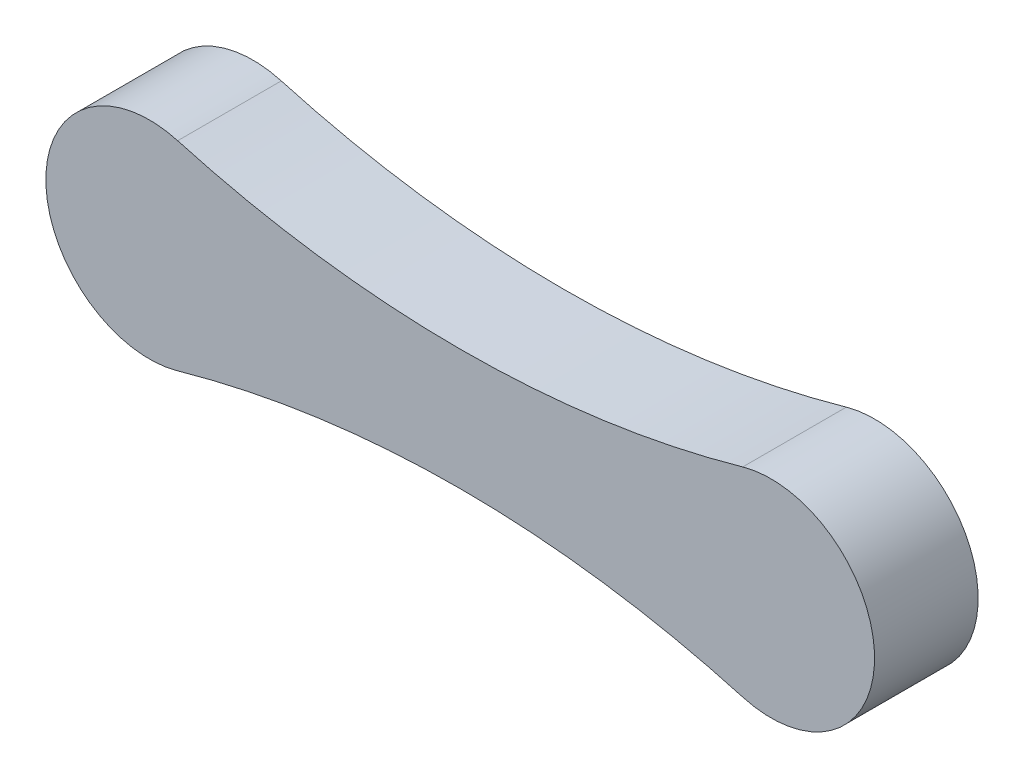
SolidWorks part; units mm, degrees
ref_plane "前视基准面" through (0, 0, 0) normal (0, 0, 1) x (1, 0, 0)
ref_plane "上视基准面" through (0, 0, 0) normal (0, 1, 0) x (1, 0, 0)
ref_plane "右视基准面" through (0, 0, 0) normal (1, 0, 0) x (0, 0, -1)
other "Configuration Table"
sketch "Sketch1" plane through (0, 0, 0) normal (0, 0, 1) x (1, 0, 0)
  line L0 (0, 0) -> (30, 0) construction
  circle A0 centre (0, 0) radius 5
  circle A2 centre (30, 0) radius 5
  arc A3 (1.3636, 4.8105) -> (28.6364, 4.8105) centre (15, 52.915) ccw
  arc A4 (1.3636, -4.8105) -> (28.6364, -4.8105) centre (15, -52.915) cw
  point P8 (30.7366, 5.456)
  dimension "D1" = 10
  dimension "D2" = 10
  dimension "D4" = 50
  dimension "D3" = 30
extrude "Boss-Extrude1" add sketch "Sketch1" along normal blind 5
